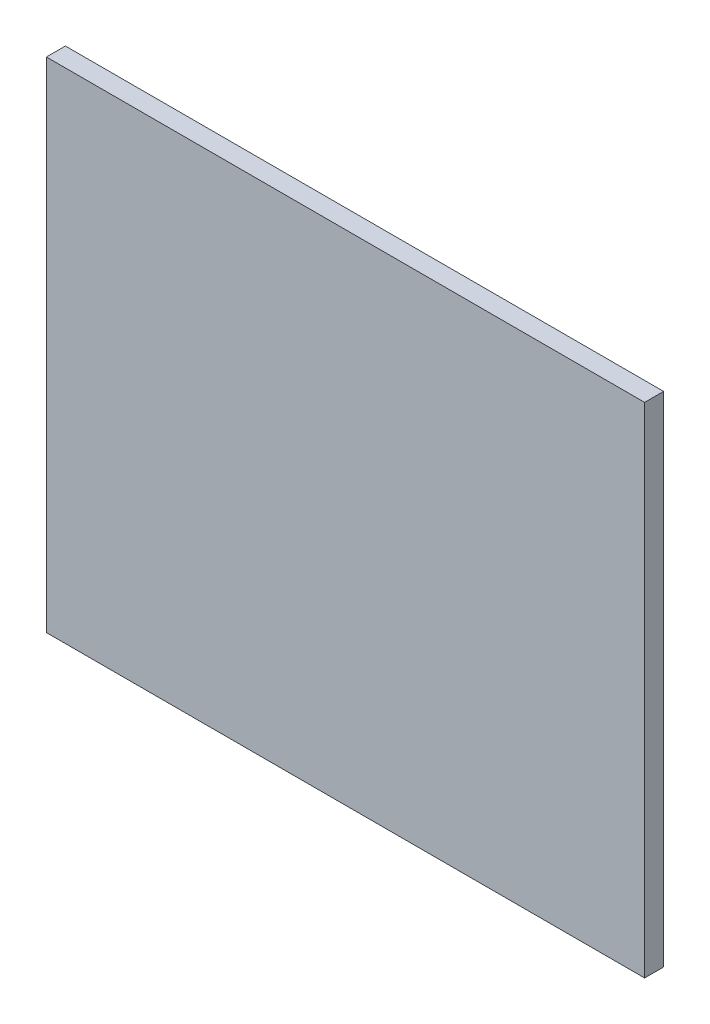
SolidWorks part; units mm, degrees
ref_plane "Front Plane" through (0, 0, 0) normal (0, 0, 1) x (1, 0, 0)
ref_plane "Top Plane" through (0, 0, 0) normal (0, 1, 0) x (1, 0, 0)
ref_plane "Right Plane" through (0, 0, 0) normal (1, 0, 0) x (0, 0, -1)
sketch "Sketch1" plane through (0, 0, 0) normal (0, 0, 1) x (1, 0, 0)
  line L0 (300, 250) -> (300, 185) construction
  line L1 (300, 250) -> (-300, 250) construction
  line L2 (300, 250) -> (300, 185)
  line L3 (300, 250) -> (-300, 250)
  line L5 (-300, -250) -> (300, -250)
  line L6 (-300, -250) -> (-300, 250)
  line L7 (-300, 250) -> (300, 250)
  line L8 (300, -250) -> (300, 250)
  dimension "D1" = 500
  dimension "D2" = 600
extrude "Boss-Extrude1" add sketch "Sketch1" along normal blind 19.05 contours L5 L8 L2 L3 L6
